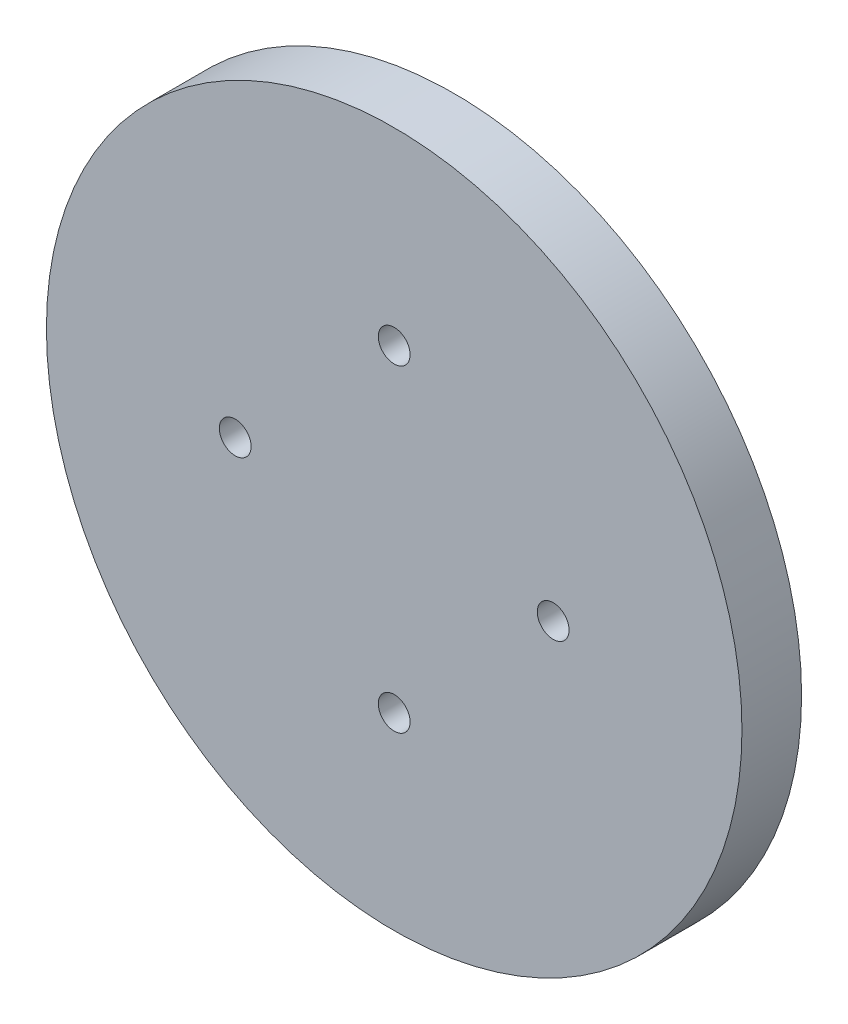
SolidWorks part; units mm, degrees
ref_plane "Plan de face" through (0, 0, 0) normal (0, 0, 1) x (1, 0, 0)
ref_plane "Plan de dessus" through (0, 0, 0) normal (0, 1, 0) x (1, 0, 0)
ref_plane "Plan de droite" through (0, 0, 0) normal (1, 0, 0) x (0, 0, -1)
sketch "Esquisse1" plane through (0, 0, 0) normal (0, 0, 1) x (1, 0, 0)
  circle A0 centre (0, 0) radius 17.5
  dimension "D1" = 35
extrude "Boss.-Extru.1" add sketch "Esquisse1" along normal blind 3
sketch "Esquisse2" plane through (0, 0, 3) normal (0, 0, 1) x (1, 0, 0)
  line L0 (0, 0) -> (0, 2.1842) construction
  circle A0 centre (0, 8) radius 0.8
  dimension "D2" = 1.6
  dimension "D1" = 8
extrude "Enlèv. mat.-Extru.1" cut sketch "Esquisse2" against normal up to surface (3 mm away) up to face at (17.5, 0, 0)
pattern_circular "Répétition circulaire1" count 4 over 360 about axis through (0, 0, 0) along (0, 0, 1) of "Enlèv. mat.-Extru.1"
